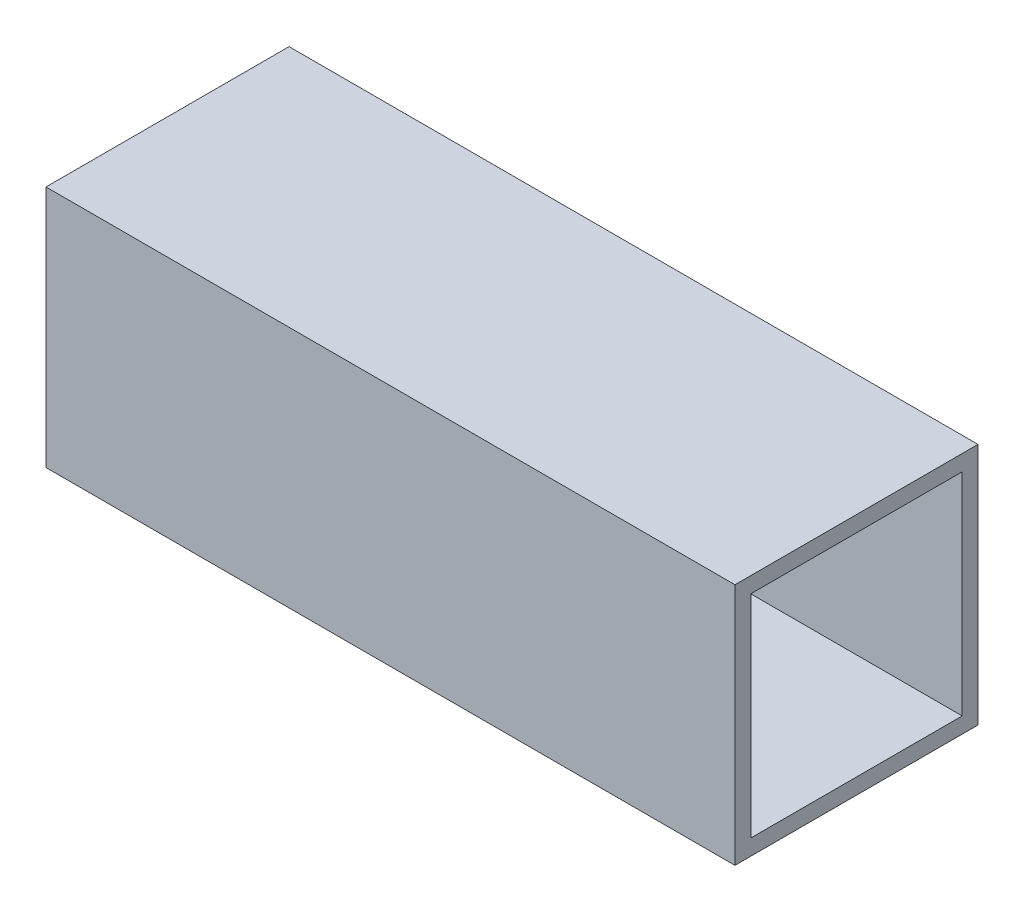
SolidWorks part; units mm, degrees
material "AISI 1010 Steel, hot rolled bar"
ref_plane "Front Plane" through (0, 0, 0) normal (0, 0, 1) x (1, 0, 0)
ref_plane "Top Plane" through (0, 0, 0) normal (0, 1, 0) x (1, 0, 0)
ref_plane "Right Plane" through (0, 0, 0) normal (1, 0, 0) x (0, 0, -1)
sketch "Sketch1" plane through (0, 0, 0) normal (0, 1, 0) x (1, 0, 0)
  line L0 (0, 0) -> (72, 0)
  dimension "D1" = 72
other "Al tube square AL TUBE 1 SQR X 0.065 WALL(1)"
ref_plane "Plane1" through (0, 0, 0) normal (1, 0, 0) x (0, 0, -1)
sketch "Sketch16" plane through (0, 0, 0) normal (1, 0, 0) x (0, 0, -1)
  line L0 (-11.049, -11.049) -> (-11.049, 11.049)
  line L1 (11.049, 11.049) -> (-11.049, 11.049)
  line L2 (11.049, 11.049) -> (11.049, -11.049)
  line L3 (-11.049, -11.049) -> (11.049, -11.049)
  line L4 (-12.7, -12.7) -> (12.7, -12.7)
  line L5 (-12.7, -12.7) -> (-12.7, 12.7)
  line L6 (12.7, 12.7) -> (-12.7, 12.7)
  line L7 (12.7, 12.7) -> (12.7, -12.7)
  line L8 (0, -11.049) -> (0, -12.7) construction
  line L9 (0, -11.049) -> (0, 11.049) construction
  line L10 (0, 11.049) -> (0, 12.7) construction
  line L11 (12.7, 0) -> (11.049, 0) construction
  line L12 (11.049, 0) -> (-11.049, 0) construction
  line L13 (-11.049, 0) -> (-12.7, 0) construction
  point P14 (0, 0)
  point P17 (0, 0)
  dimension "Thickness" = 1.651
  dimension "V_leg" = 25.4
  dimension "H_leg" = 25.4
